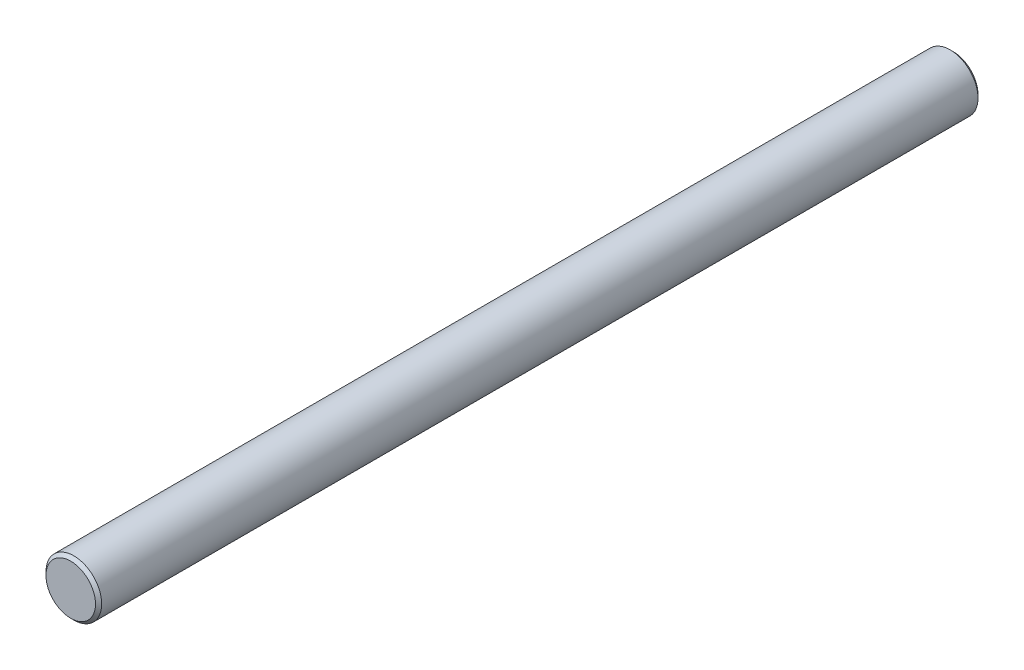
SolidWorks part; units mm, degrees
ref_plane "Front" through (0, 0, 0) normal (0, 0, 1) x (1, 0, 0)
ref_plane "Top" through (0, 0, 0) normal (0, 1, 0) x (1, 0, 0)
ref_plane "Right" through (0, 0, 0) normal (1, 0, 0) x (0, 0, -1)
sketch "Sketch1" plane through (0, 0, 0) normal (0, 0, 1) x (1, 0, 0)
  circle A0 centre (0, 0) radius 2.286
  dimension "D1" = 4.572
extrude "Boss-Extrude1" add sketch "Sketch1" along normal blind 72.39
chamfer "Chamfer1" distance 0.254 angle 45 2 edges at (2.286, 0, 0) (2.286, 0, 72.39)
